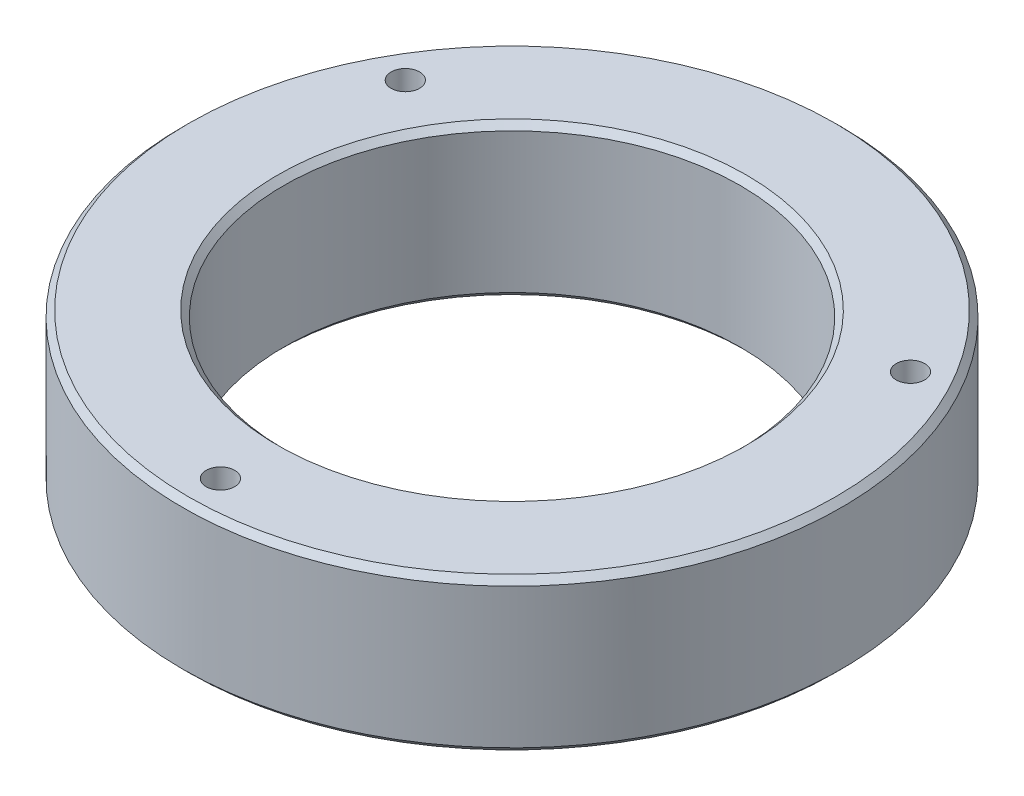
SolidWorks part; units mm, degrees
ref_plane "Front Plane" through (0, 0, 0) normal (1, 0, 0) x (0, 1, 0)
ref_plane "Top Plane" through (0, 0, 0) normal (0, 0, 1) x (0, 1, 0)
ref_plane "Right Plane" through (0, 0, 0) normal (0, 1, 0) x (-1, 0, 0)
sketch "Sketch1" plane through (0, 0, 0) normal (0, 0, 1) x (0, 1, 0)
  line L0 (-19.05, 82.5246) -> (19.05, 82.5246)
  line L1 (19.05, 82.5246) -> (19.05, 57.15)
  line L2 (19.05, 57.15) -> (-19.05, 57.15)
  line L3 (-19.05, 57.15) -> (-19.05, 82.5246)
  line L4 (-44.45, 0) -> (44.45, 0) construction
revolve "Revolve1" add sketch "Sketch1" angle 360 about L4
hole_wizard "CBORE for 1/4 Socket Head Cap Screw1" positions "Sketch3" profile "Sketch2" counterbore size "1/4" standard "ANSI Inch"
sketch "Sketch3" plane through (0, -19.05, 0) normal (0, -1, 0) x (-1, 0, 0)
  circle A0 centre (0, 0.0068) radius 73.0318 construction
  point P0 (0, -73.025)
  point P1 (-63.246, 36.5252)
  point P3 (63.246, 36.5252)
sketch "Sketch2" plane through (0, -19.05, 73.025) normal (1, 0, 0) x (0, 0, -1)
  line L0 (0, 0) -> (0, 40.2443)
  line L1 (0, 40.2443) -> (3.5687, 38.1)
  line L2 (3.5687, 38.1) -> (3.5687, 9.652)
  line L3 (3.5687, 9.652) -> (5.5626, 9.652)
  line L4 (5.5626, 9.652) -> (5.5626, 0)
  line L5 (5.5626, 0) -> (0, 0)
  line L10 (0, 40.2443) -> (-3.5687, 38.1) construction
  line L11 (0, -6.35) -> (0, 107.95) construction
  dimension "Hole Dia." = 7.1374
  dimension "Hole Depth" = 38.1
  dimension "C'Bore Dia." = 11.1252
  dimension "C'Bore Depth" = 9.652
  dimension "Drill Angle" = 118
hole_wizard "3/8-16 Tapped Hole2" positions "Sketch7" profile "Sketch6" tap size "3/8-16" standard "ANSI Inch"
sketch "Sketch7" plane through (0, -19.05, 0) normal (0, -1, 0) x (-1, 0, 0)
  point P0 (-69.85, 0)
  point P1 (69.85, 0)
sketch "Sketch6" plane through (69.85, -19.05, 0) normal (1, 0, 0) x (0, 0, -1)
  line L0 (0, 0) -> (0, 27.7847)
  line L1 (0, 27.7847) -> (3.9687, 25.4)
  line L2 (3.9687, 25.4) -> (3.9687, 0)
  line L5 (3.9687, 0) -> (0, 0)
  line L10 (0, 27.7847) -> (-3.9687, 25.4) construction
  line L11 (0, -6.35) -> (0, 107.95) construction
  dimension "Tap Drill Dia." = 7.9375
  dimension "Tap Drill Depth" = 25.4
  dimension "Drill Angle" = 118
cosmetic thread "Hole Thread3" parameters "D1"=19.05, "D2"=9.525
cosmetic thread "Hole Thread4" parameters "D1"=19.05, "D2"=9.525
chamfer "Chamfer1" distance 1.524 angle 45 4 edges at (0, 19.05, -57.15) (0, -19.05, -57.15) (0, 19.05, -82.5246) (0, -19.05, -82.5246)
